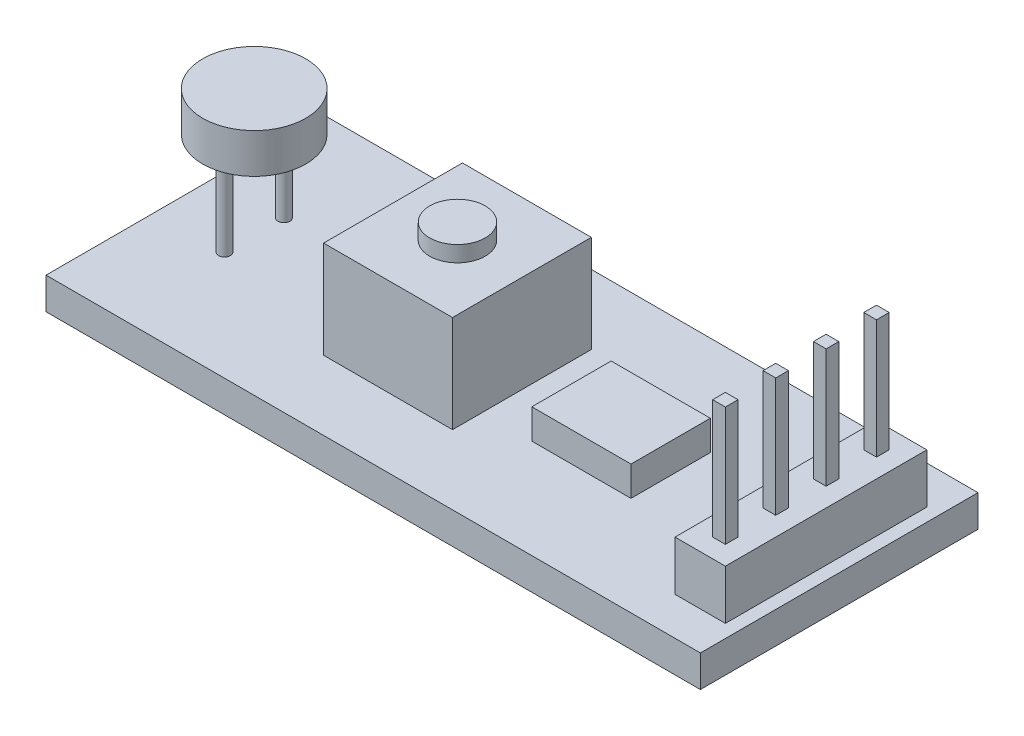
SolidWorks part; units mm, degrees
ref_plane "Front Plane" through (0, 0, 0) normal (0, 0, 1) x (1, 0, 0)
ref_plane "Top Plane" through (0, 0, 0) normal (0, 1, 0) x (1, 0, 0)
ref_plane "Right Plane" through (0, 0, 0) normal (1, 0, 0) x (0, 0, -1)
sketch "SK PCB" plane through (0, 0, 0) normal (0, 1, 0) x (1, 0, 0)
  line L1 (0, 14) -> (33, 14)
  line L2 (0, 14) -> (0, 0)
  line L3 (0, 0) -> (33, 0)
  line L4 (33, 14) -> (33, 0)
extrude "PCB" add sketch "SK PCB" along normal blind 1.6 separate body
sketch "SK LDR legs" plane through (0, 0, 0) normal (0, 1, 0) x (1, 0, 0)
  circle A0 centre (3.5, 5.5) radius 0.3
  circle A1 centre (3.5, 8.5) radius 0.3
extrude "LDR legs" add sketch "SK LDR legs" along normal blind 4.4 from offset 1.6 separate body
sketch "SK LDR cell" plane through (0, 0, 0) normal (0, 1, 0) x (1, 0, 0)
  circle A0 centre (3.5, 7) radius 2.6
extrude "LDR cell" add sketch "SK LDR cell" along normal blind 2 from offset 6 separate body
sketch "SK Trim pot" plane through (0, 0, 0) normal (0, 1, 0) x (1, 0, 0)
  line L1 (10.5, 10.5) -> (17, 10.5)
  line L2 (10.5, 10.5) -> (10.5, 3.5)
  line L3 (10.5, 3.5) -> (17, 3.5)
  line L4 (17, 10.5) -> (17, 3.5)
extrude "Trim pot" add sketch "SK Trim pot" along normal blind 4.9 from offset 1.6 separate body
sketch "SK Pot screw" plane through (0, 0, 0) normal (0, 1, 0) x (1, 0, 0)
  circle A0 centre (13.75, 7) radius 1.4
extrude "Pot screw" add sketch "SK Pot screw" along normal blind 0.8 from offset 6.5 separate body
sketch "SK LM393" plane through (0, 0, 0) normal (0, 1, 0) x (1, 0, 0)
  line L1 (19.5, 9) -> (24.5, 9)
  line L2 (19.5, 9) -> (19.5, 5)
  line L3 (19.5, 5) -> (24.5, 5)
  line L4 (24.5, 9) -> (24.5, 5)
extrude "LM393" add sketch "SK LM393" along normal blind 1.5 from offset 1.6 separate body
sketch "SK Header 4 pin" plane through (0, 0, 0) normal (0, 1, 0) x (1, 0, 0)
  line L1 (29.8, 12.08) -> (32.34, 12.08)
  line L2 (29.8, 12.08) -> (29.8, 1.92)
  line L3 (29.8, 1.92) -> (32.34, 1.92)
  line L4 (32.34, 12.08) -> (32.34, 1.92)
extrude "Header 4 pin" add sketch "SK Header 4 pin" along normal blind 2.5 from offset 1.6 separate body
sketch "SK Header pins" plane through (0, 0, 0) normal (0, 1, 0) x (1, 0, 0)
  line L1 (30.75, 11.13) -> (31.39, 11.13)
  line L2 (30.75, 11.13) -> (30.75, 10.49)
  line L3 (30.75, 10.49) -> (31.39, 10.49)
  line L4 (31.39, 11.13) -> (31.39, 10.49)
  line L6 (30.75, 8.59) -> (31.39, 8.59)
  line L7 (30.75, 8.59) -> (30.75, 7.95)
  line L8 (30.75, 7.95) -> (31.39, 7.95)
  line L9 (31.39, 8.59) -> (31.39, 7.95)
  line L11 (30.75, 6.05) -> (31.39, 6.05)
  line L12 (30.75, 6.05) -> (30.75, 5.41)
  line L13 (30.75, 5.41) -> (31.39, 5.41)
  line L14 (31.39, 6.05) -> (31.39, 5.41)
  line L16 (30.75, 3.51) -> (31.39, 3.51)
  line L17 (30.75, 3.51) -> (30.75, 2.87)
  line L18 (30.75, 2.87) -> (31.39, 2.87)
  line L19 (31.39, 3.51) -> (31.39, 2.87)
extrude "Header pins" add sketch "SK Header pins" along normal blind 6 from offset 4.1 separate body
